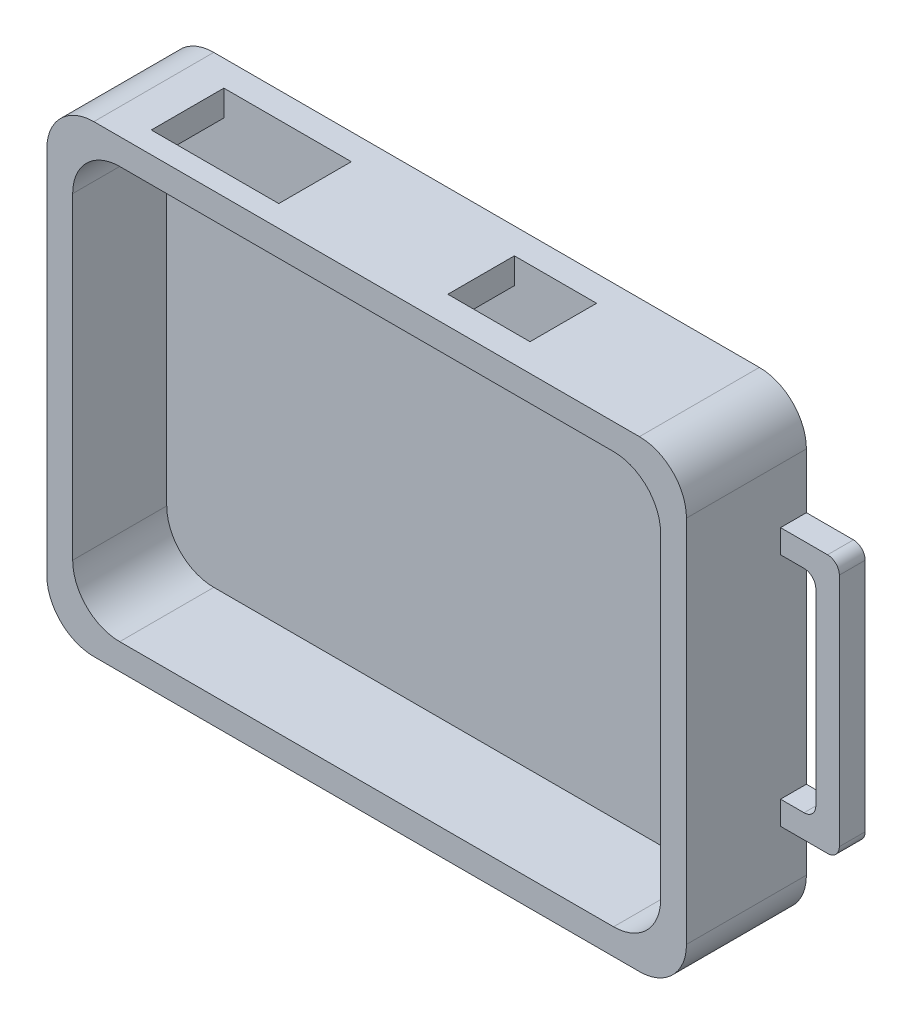
SolidWorks part; units mm, degrees
material "PET"
ref_plane "Front Plane" through (0, 0, 0) normal (0, 0, 1) x (1, 0, 0)
ref_plane "Top Plane" through (0, 0, 0) normal (0, 1, 0) x (1, 0, 0)
ref_plane "Right Plane" through (0, 0, 0) normal (1, 0, 0) x (0, 0, -1)
sketch "Sketch1" plane through (0, 0, 0) normal (0, 0, 1) x (1, 0, 0)
  line L1 (23.2, -19.7) -> (-23.2, -19.7)
  line L2 (27.2, -15.7) -> (27.2, 15.7)
  line L3 (23.2, 19.7) -> (-23.2, 19.7)
  line L4 (-27.2, -15.7) -> (-27.2, 15.7)
  line L5 (27.2, -19.7) -> (-27.2, 19.7) construction
  line L6 (27.2, 19.7) -> (-27.2, -19.7) construction
  arc A0 (-23.2, 19.7) -> (-27.2, 15.7) centre (-23.2, 15.7) ccw
  arc A1 (27.2, 15.7) -> (23.2, 19.7) centre (23.2, 15.7) ccw
  arc A2 (23.2, -19.7) -> (27.2, -15.7) centre (23.2, -15.7) ccw
  arc A3 (-27.2, -15.7) -> (-23.2, -19.7) centre (-23.2, -15.7) ccw
  point P0 (0, 0)
  dimension "D3" = 4
  dimension "D4" = 4
  dimension "D5" = 4
  dimension "D6" = 4
  dimension "D1" = 54.4
  dimension "D2" = 39.4
extrude "Boss-Extrude1" add sketch "Sketch1" along normal blind 10.2
sketch "Sketch2" plane through (0, 0, 10.2) normal (0, 0, 1) x (1, 0, 0)
  line L0 (-23.2, -19.7) -> (23.2, -19.7) construction
  line L1 (21, -17.5) -> (-21, -17.5)
  line L2 (25, -13.5) -> (25, 13.5)
  line L3 (21, 17.5) -> (-21, 17.5)
  line L4 (-25, -13.5) -> (-25, 13.5)
  line L5 (25, -17.5) -> (-25, 17.5) construction
  line L6 (25, 17.5) -> (-25, -17.5) construction
  line L7 (27.2, -15.7) -> (27.2, 15.7) construction
  arc A0 (-21, 17.5) -> (-25, 13.5) centre (-21, 13.5) ccw
  arc A1 (25, 13.5) -> (21, 17.5) centre (21, 13.5) ccw
  arc A2 (21, -17.5) -> (25, -13.5) centre (21, -13.5) ccw
  arc A3 (-25, -13.5) -> (-21, -17.5) centre (-21, -13.5) ccw
  point P0 (0, 0)
  dimension "D3" = 4
  dimension "D4" = 4
  dimension "D5" = 4
  dimension "D6" = 4
  dimension "D1" = 2.2
  dimension "D2" = 2.2
extrude "Cut-Extrude1" cut sketch "Sketch2" against normal blind 8
sketch "Sketch4" plane through (0, 0, 2.2) normal (0, 0, 1) x (1, 0, 0)
  line L0 (-27.2, 0) -> (33.7154, 0) construction
  line L1 (-27.2, 15.7) -> (-27.2, -15.7) construction
  line L2 (27.2, -15.7) -> (27.2, 15.7) construction
  line L3 (27.2, -11) -> (31.2, -11)
  line L5 (27.2, 11) -> (31.2, 11)
  line L6 (32.2, -10) -> (32.2, 10)
  line L7 (0, 21.5479) -> (0, -22.147) construction
  line L8 (-27.2, 11) -> (-27.2, -11)
  line L9 (27.2, 11) -> (27.2, -11)
  line L10 (-27.2, -11) -> (-31.2, -11)
  line L11 (-32.2, -10) -> (-32.2, 10)
  line L12 (-27.2, 11) -> (-31.2, 11)
  arc A0 (32.2, -10) -> (31.2, -11) centre (31.2, -10) cw
  arc A1 (32.2, 10) -> (31.2, 11) centre (31.2, 10) ccw
  arc A2 (-32.2, -10) -> (-31.2, -11) centre (-31.2, -10) ccw
  arc A3 (-32.2, 10) -> (-31.2, 11) centre (-31.2, 10) cw
  point P5 (27.2, 0)
  point P14 (32.2, -11)
  point P17 (32.2, 11)
  dimension "D3" = 1
  dimension "D1" = 22
  dimension "D2" = 5
extrude "Boss-Extrude2" add sketch "Sketch4" against normal blind 2.2
sketch "Sketch5" plane through (0, 0, 2.2) normal (0, 0, 1) x (1, 0, 0)
  line L0 (0, 23.7466) -> (0, -22.9849) construction
  line L1 (31.2, 11) -> (27.2, 11) construction
  line L2 (27.2, -11) -> (31.2, -11) construction
  line L3 (27.2, -9) -> (29.2, -9)
  line L4 (27.2, -9) -> (27.2, 9)
  line L5 (27.2, 9) -> (29.2, 9)
  line L6 (30.2, -8) -> (30.2, 8)
  line L7 (-27.2, -9) -> (-27.2, 9)
  line L8 (-27.2, -9) -> (-29.2, -9)
  line L9 (32.2, -10) -> (32.2, 10) construction
  line L10 (-30.2, -8) -> (-30.2, 8)
  line L11 (-27.2, 9) -> (-29.2, 9)
  arc A0 (30.2, 8) -> (29.2, 9) centre (29.2, 8) ccw
  arc A1 (29.2, -9) -> (30.2, -8) centre (29.2, -8) ccw
  arc A2 (-29.2, -9) -> (-30.2, -8) centre (-29.2, -8) cw
  arc A3 (-30.2, 8) -> (-29.2, 9) centre (-29.2, 8) cw
  dimension "D4" = 1
  dimension "D5" = 1
  dimension "D1" = 2
  dimension "D2" = 2
  dimension "D3" = 2
extrude "Cut-Extrude2" cut sketch "Sketch5" against normal blind 2.2
sketch "Sketch6" plane through (0, 0, 0) normal (0, 1, 0) x (1, 0, 0)
  line L7 (-20.141, -2.2) -> (-9.301, -2.2)
  line L9 (-20.141, -2.2) -> (-20.141, -8.37)
  line L10 (-20.141, -8.37) -> (-9.301, -8.37)
  line L11 (-9.301, -2.2) -> (-9.301, -8.37)
  dimension "D2" = 10.84
extrude "Cut-Extrude3" cut sketch "Sketch6" along normal blind 46
sketch "Sketch8" plane through (0, 0, 0) normal (0, 1, 0) x (1, 0, 0)
  line L2 (4.5649, -2.2) -> (11.5549, -2.2)
  line L3 (11.5549, -7.86) -> (4.5649, -7.86)
  line L4 (11.5549, -7.86) -> (11.5549, -2.2)
  line L6 (4.5649, -7.86) -> (4.5649, -2.2)
  dimension "D2" = 6.99
extrude "Cut-Extrude4" cut sketch "Sketch8" along normal blind 29
